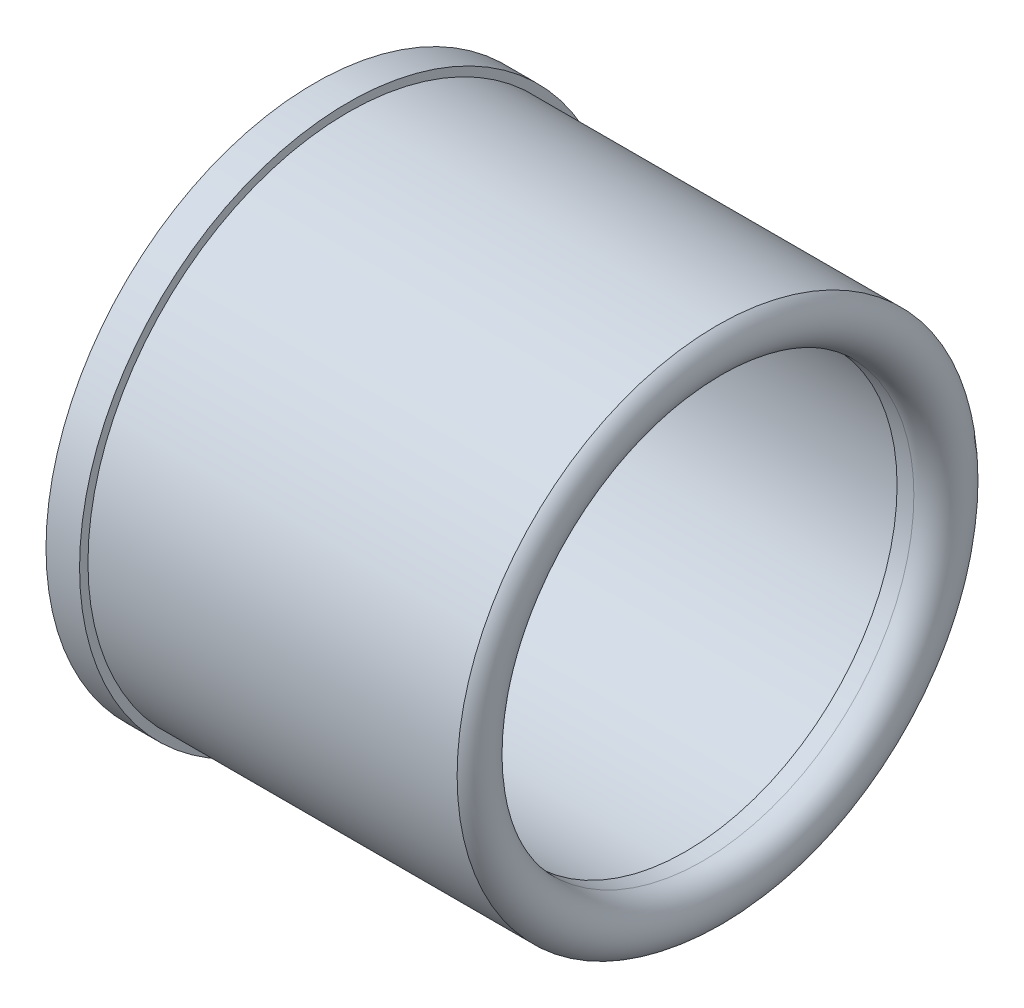
SolidWorks part; units mm, degrees
ref_plane "Front Plane" through (0, 0, 0) normal (0, 0, 1) x (1, 0, 0)
ref_plane "Top Plane" through (0, 0, 0) normal (0, 1, 0) x (1, 0, 0)
ref_plane "Right Plane" through (0, 0, 0) normal (1, 0, 0) x (0, 0, -1)
ref_plane "Plane1" through (0, 0, 0) normal (0, 0, -1) x (-1, 0, 0)
sketch "Sketch1" plane through (0, 0, 0) normal (0, 0, -1) x (-1, 0, 0)
  line L0 (-11.9728, -2.2333) -> (-11.9728, -1.9833)
  line L1 (-11.9728, -1.9833) -> (-0.9121, -1.9833)
  line L2 (-0.9121, -1.9833) -> (-0.9121, -0.5333)
  line L3 (-0.9121, -0.5333) -> (-1.9121, -0.5333)
  line L4 (-1.9121, -0.5333) -> (-1.9121, -0.7833)
  line L5 (-1.9121, -0.7833) -> (-12.9121, -0.7833)
  line L6 (-12.4728, -2.2333) -> (-11.9728, -2.2333)
  line L7 (-12.1757, -8.5333) -> (0.2029, -8.5333) construction
  arc A0 (-12.9121, -0.7833) -> (-12.4728, -2.2333) centre (-12.4728, -1.4417) ccw
  dimension "D1" = 11
  dimension "D2" = 1.45
  dimension "D3" = 0.25
  dimension "D4" = 0.25
  dimension "D5" = 13.1
  dimension "D6" = 1
  dimension "D7" = 0.5
revolve "Revolve1" add sketch "Sketch1" angle 360 about L7
